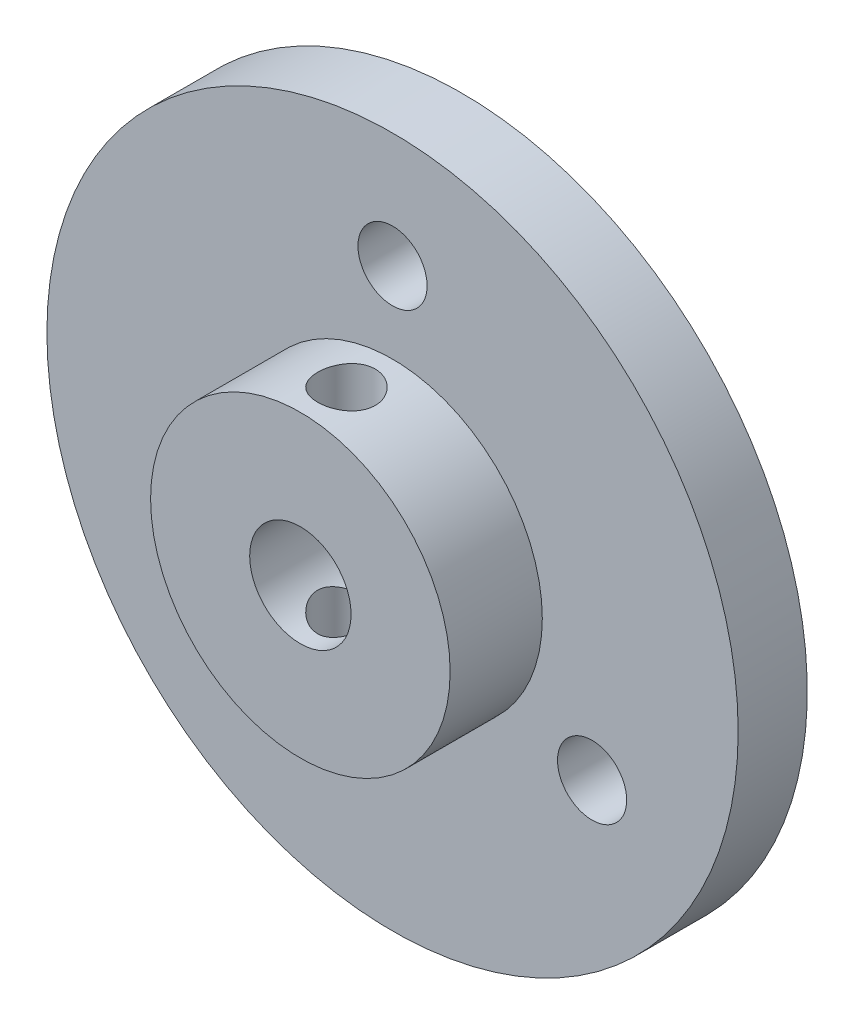
SolidWorks part; units mm, degrees
ref_plane "Front Plane" through (0, 0, 0) normal (0, 0, 1) x (1, 0, 0)
ref_plane "Top Plane" through (0, 0, 0) normal (0, 1, 0) x (1, 0, 0)
ref_plane "Right Plane" through (0, 0, 0) normal (1, 0, 0) x (0, 0, -1)
sketch "Sketch1" plane through (0, 0, 0) normal (0, 0, 1) x (1, 0, 0)
  line L1 (0, 0) -> (0, 10) construction
  circle A0 centre (0, 0) radius 15
  circle A1 centre (0, 0) radius 2.2
  circle A3 centre (0, 10) radius 1.5
  circle A4 centre (8.6603, -5) radius 1.5
  circle A5 centre (-8.6603, -5) radius 1.5
  point P4 (2.2, 0)
  point P6 (0, 0)
  point P15 (0, 0)
  dimension "D1" = 30
  dimension "D2" = 3
  dimension "D4" = 4.4
  dimension "D3" = 3
  dimension "D5" = 10
extrude "Boss-Extrude1" add sketch "Sketch1" along normal blind 5
sketch "Sketch2" plane through (0, 0, 5) normal (0, 0, 1) x (1, 0, 0)
  circle A0 centre (0, 0) radius 6.5
  circle A1 centre (0, 0) radius 2.2 construction
  circle A2 centre (0, 0) radius 2.2
  circle M4 centre (0, 0) radius 2.2
  dimension "D1" = 13
extrude "Boss-Extrude2" add sketch "Sketch2" along normal blind 4 contours A0 M4
sketch "Sketch3" plane through (0, 0, 9) normal (0, 0, 1) x (1, 0, 0)
  line L0 (0, 2.2) -> (0, 6.5) construction
  line L2 (-3, 3.1) -> (3, 3.1)
  line L3 (-3, 3.1) -> (-3, 5.6)
  line L4 (-3, 5.6) -> (3, 5.6)
  line L5 (3, 3.1) -> (3, 5.6)
  line L6 (-3, 3.1) -> (3, 5.6) construction
  line L7 (-3, 5.6) -> (3, 3.1) construction
  circle A0 centre (0, 0) radius 2.2 construction
  circle A1 centre (0, 0) radius 6.5 construction
  point P7 (0, 4.35)
  dimension "D1" = 6
  dimension "D2" = 2.5
sketch "Sketch4" plane through (0, 0, 5) normal (0, 0, 1) x (1, 0, 0)
  line L0 (-4.5, 4.6904) -> (4.5, 4.6904)
  line L1 (-4.5, 4.6904) -> (-4.5, 7.6904)
  line L2 (4.5, 4.6904) -> (4.5, 7.6904)
  line L3 (-4.5, 7.6904) -> (4.5, 7.6904)
  line L4 (0, 0) -> (2.2, 0) construction
  circle A0 centre (0, 0) radius 6.5 construction
  circle A1 centre (0, 0) radius 2.2 construction
  circle M6 centre (0, 0) radius 6.5
  dimension "D1" = 9
  dimension "D2" = 3
extrude "Boss-Extrude3" add sketch "Sketch4" along normal up to surface (4 mm away) contours L3 L1 L2 M6 up to face at (2.2, 0, 9)
extrude "Cut-Extrude1" cut sketch "Sketch3" along direction (0, 0, 1) on the side against the normal through all contours L2 L5 L4 L3
sketch "Sketch5" plane through (0, 7.6904, 0) normal (0, 1, 0) x (1, 0, 0)
  line L0 (0, -5) -> (0, -9) construction
  line L1 (-4.5, -5) -> (4.5, -5) construction
  line L2 (-4.5, -9) -> (4.5, -9) construction
  circle A0 centre (0, -7) radius 1.25
  dimension "D1" = 2.5
extrude "Cut-Extrude2" cut sketch "Sketch5" against normal blind 7
sketch "Sketch6" plane through (-3, 0, 0) normal (1, 0, 0) x (0, 0, -1)
  line L4 (-9, 5.6) -> (-9, 3.1)
  line L5 (-9, 3.1) -> (0, 3.1)
  line L6 (0, 3.1) -> (0, 5.6)
  line L7 (0, 5.6) -> (-9, 5.6)
  line L8 (-9, 5.6) -> (-9, 3.1)
  line L9 (-9, 3.1) -> (0, 3.1)
  line L10 (0, 3.1) -> (0, 5.6)
  line L11 (0, 5.6) -> (-9, 5.6)
  dimension "D1" = 0
extrude "Boss-Extrude4" add sketch "Sketch6" along normal up to surface (6 mm away) contours L8 L9 L10 L11 up to face at (3, 4.35, 4.5)
sketch "Sketch7" plane through (0, 0, 9) normal (0, 0, 1) x (1, 0, 0)
  circle A0 centre (0, 0) radius 6.5
  arc A1 (-4.5, 4.6904) -> (4.5, 4.6904) centre (0, 0) ccw construction
  line M3 (4.5, 4.6904) -> (4.5, 7.6904)
  line M4 (4.5, 7.6904) -> (-4.5, 7.6904)
  line M5 (-4.5, 7.6904) -> (-4.5, 4.6904)
extrude "Cut-Extrude3" cut sketch "Sketch7" along direction (0, 0, 1) on the side against the normal up to surface (4 mm away) contours A0 M3 M4 M5
sketch "Sketch8" plane through (0, 5.6, 0) normal (0, 1, 0) x (1, 0, 0)
  circle A1 centre (0, -7) radius 1.25
  circle A2 centre (0, -7) radius 1.25
  dimension "D1" = 0
extrude "Cut-Extrude4" cut sketch "Sketch8" against normal blind 14 and the other way blind 2 contours A2
sketch "Sketch9" plane through (0, 0, 0) normal (0, 0, -1) x (-1, 0, 0)
  circle A1 centre (0, 0) radius 15
  circle A2 centre (0, 0) radius 15
  dimension "D1" = 0
extrude "Cut-Extrude5" cut sketch "Sketch9" against normal blind 2 contours A2
